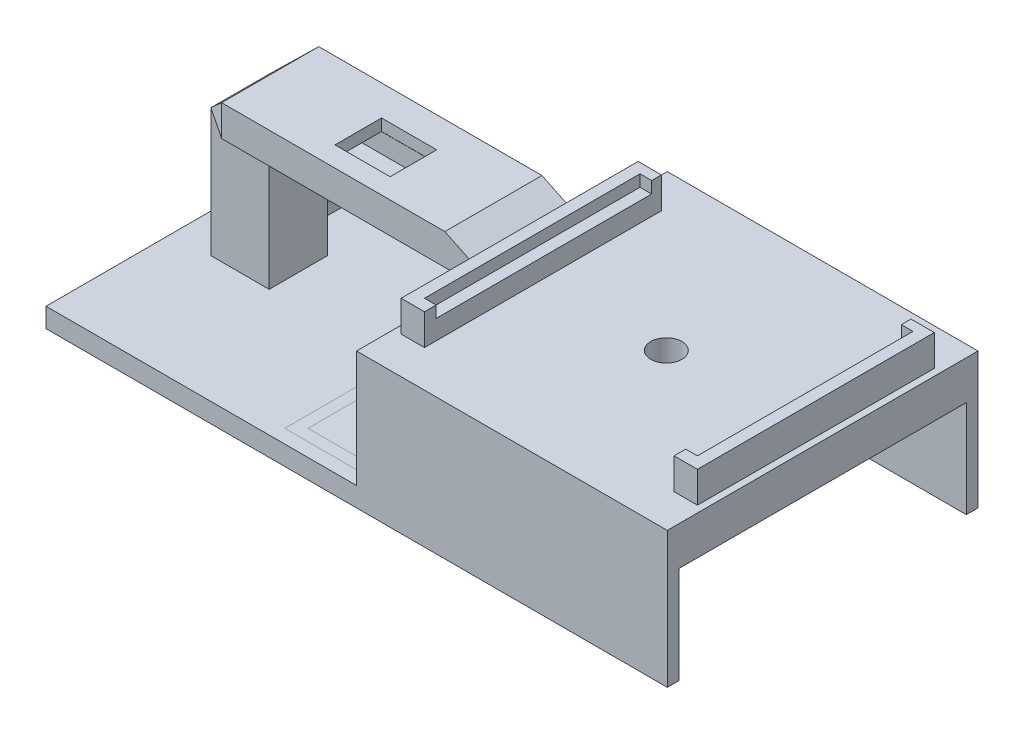
SolidWorks part; units mm, degrees
ref_plane "Plan de face" through (0, 0, 0) normal (0, 0, 1) x (1, 0, 0)
ref_plane "Plan de dessus" through (0, 0, 0) normal (0, 1, 0) x (1, 0, 0)
ref_plane "Plan de droite" through (0, 0, 0) normal (1, 0, 0) x (0, 0, -1)
sketch "Esquisse1" plane through (0, 0, 0) normal (0, 1, 0) x (1, 0, 0)
  line L1 (-75, 40) -> (75, 40)
  line L2 (-75, 40) -> (-75, -40)
  line L3 (-75, -40) -> (75, -40)
  line L4 (75, 40) -> (75, -40)
  line L5 (-75, 40) -> (75, -40) construction
  line L6 (-75, -40) -> (75, 40) construction
  point P0 (0, 0)
  dimension "D1" = 80
  dimension "D2" = 150
extrude "Boss.-Extru.1" add sketch "Esquisse1" along normal blind 5
sketch "Esquisse2" plane through (0, 5, 0) normal (0, 1, 0) x (1, 0, 0)
  line L0 (-75, -40) -> (75, -40) construction
  line L1 (75, 40) -> (-5, 40)
  line L2 (75, 40) -> (75, -40)
  line L3 (75, -40) -> (-5, -40)
  line L4 (-5, 40) -> (-5, -40)
  dimension "D1" = 80
extrude "Boss.-Extru.2" add sketch "Esquisse2" along normal blind 30
sketch "Esquisse3" plane through (0, 0, 0) normal (0, -1, 0) x (1, 0, 0)
  line L0 (75, -40) -> (-75, -40) construction
  line L1 (75, 40) -> (0, 40)
  line L2 (75, 40) -> (75, -40)
  line L3 (75, -40) -> (0, -40)
  line L4 (0, 40) -> (0, -40)
  dimension "D1" = 75
extrude "Enlèv. mat.-Extru.1" cut sketch "Esquisse3" against normal blind 25
sketch "Esquisse6" plane through (0, 35, 0) normal (0, 1, 0) x (1, 0, 0)
  circle A0 centre (34.7534, 0) radius 4
  dimension "D1" = 8
extrude "Enlèv. mat.-Extru.2" cut sketch "Esquisse6" against normal blind 40
sketch "Esquisse7" plane through (0, 35, 0) normal (0, 1, 0) x (1, 0, 0)
  line L0 (-5, 0) -> (75, 0) construction
  line L1 (-5, 40) -> (-5, -40) construction
  line L2 (75, -40) -> (75, 40) construction
  line L3 (70.2558, 0) -> (-0.0157, 0) construction
  line L4 (-3.0157, -30.5) -> (2.9843, -30.5)
  line L5 (-3.0157, -30.5) -> (-3.0157, 30.5)
  line L6 (-3.0157, 30.5) -> (2.9843, 30.5)
  line L7 (2.9843, -30.5) -> (2.9843, 30.5)
  line L8 (-3.0157, -30.5) -> (2.9843, 30.5) construction
  line L9 (-3.0157, 30.5) -> (2.9843, -30.5) construction
  line L10 (73.2558, -30.5) -> (67.2558, -30.5)
  line L11 (73.2558, -30.5) -> (73.2558, 30.5)
  line L12 (73.2558, 30.5) -> (67.2558, 30.5)
  line L13 (67.2558, -30.5) -> (67.2558, 30.5)
  line L14 (73.2558, -30.5) -> (67.2558, 30.5) construction
  line L15 (73.2558, 30.5) -> (67.2558, -30.5) construction
  point P6 (-0.0157, 0)
  point P11 (70.2558, 0)
  dimension "D1" = 6
  dimension "D2" = 61
  dimension "D3" = 6
  dimension "D4" = 61
  dimension "D5" = 69.9339
extrude "Boss.-Extru.3" add sketch "Esquisse7" along normal blind 8
sketch "Esquisse9" plane through (0, 5, 0) normal (0, 1, 0) x (1, 0, 0)
  line L0 (-5, 40) -> (-5, -40) construction
  line L1 (-5, -36.4789) -> (-27, -36.4789)
  line L2 (-5, -36.4789) -> (-5, -33.4789)
  line L3 (-5, -33.4789) -> (-27, -33.4789)
  line L4 (-27, -36.4789) -> (-27, -33.4789)
  line L6 (-27, -33.4789) -> (-24, -33.4789)
  line L7 (-27, -33.4789) -> (-27, 16.5211)
  line L8 (-27, 16.5211) -> (-24, 16.5211)
  line L9 (-24, -33.4789) -> (-24, 16.5211)
  line M4 (-5, -40) -> (-5, 40)
  dimension "D1" = 3
  dimension "D2" = 22
  dimension "D3" = 3
  dimension "D4" = 50
extrude "Boss.-Extru.4" add sketch "Esquisse9" along normal blind 0.0001 contours L4 L1 L3 M4 | L3 L9 L8 L7
sketch "Esquisse10" plane through (0, 43, 0) normal (0, 1, 0) x (1, 0, 0)
  line L0 (-0.0157, -30.5) -> (-0.0157, -27.5) construction
  line L1 (-3.0157, -30.5) -> (2.9843, -30.5) construction
  line L3 (-0.0157, -27.5) -> (2.9843, -27.5)
  line L4 (-0.0157, -27.5) -> (-0.0157, 28)
  line L5 (-0.0157, 28) -> (2.9843, 28)
  line L6 (2.9843, -27.5) -> (2.9843, 28)
  dimension "D1" = 3
  dimension "D2" = 3
  dimension "D3" = 55.5
extrude "Enlèv. mat.-Extru.3" cut sketch "Esquisse10" against normal blind 3
sketch "Esquisse11" plane through (0, 43, 0) normal (0, 1, 0) x (1, 0, 0)
  line L0 (70.2558, -30.5) -> (70.2558, -27.5) construction
  line L1 (67.2558, -30.5) -> (73.2558, -30.5) construction
  line L2 (67.2558, 30.5) -> (67.2558, -30.5) construction
  line L3 (70.2558, -27.5) -> (67.2558, -27.5)
  line L4 (70.2558, -27.5) -> (70.2558, 28)
  line L5 (70.2558, 28) -> (67.2558, 28)
  line L6 (67.2558, -27.5) -> (67.2558, 28)
  dimension "D1" = 3
  dimension "D2" = 55.5
extrude "Enlèv. mat.-Extru.4" cut sketch "Esquisse11" against normal blind 3
sketch "Esquisse12" plane through (0, 5, 0) normal (0, 1, 0) x (1, 0, 0)
  line L0 (-75, 0) -> (-5, 0) construction
  line L1 (-75, 40) -> (-75, -40) construction
  line L2 (-5, 40) -> (-5, -33.4789) construction
  line L4 (-60, -7.5) -> (-75, -7.5)
  line L5 (-60, -7.5) -> (-60, 7.5)
  line L6 (-60, 7.5) -> (-75, 7.5)
  line L7 (-75, -7.5) -> (-75, 7.5)
  line L8 (-60, -7.5) -> (-75, 7.5) construction
  line L9 (-60, 7.5) -> (-75, -7.5) construction
  point P7 (-67.5, 0)
  dimension "D1" = 15
  dimension "D2" = 15
extrude "Boss.-Extru.5" add sketch "Esquisse12" along normal blind 40
sketch "Esquisse13" plane through (0, 45, 0) normal (0, 1, 0) x (1, 0, 0)
  line L0 (-22.7295, -13.0071) -> (-66.7295, -13.0071)
  line L5 (-22.7295, -13.0071) -> (-22.7295, 11.9929)
  line L6 (-66.7295, -13.0071) -> (-66.7295, 11.9929)
  line L7 (-22.7295, 11.9929) -> (-66.7295, 11.9929)
  line L8 (-22.7295, -13.0071) -> (-66.7295, 11.9929) construction
  line L9 (-66.7295, -13.0071) -> (-22.7295, 11.9929) construction
  point P1 (-44.7295, -0.5071)
  dimension "D1" = 25
  dimension "D2" = 44
extrude "Boss.-Extru.6" add sketch "Esquisse13" along normal blind 1 and the other way blind 7
sketch "Esquisse14" plane through (0, 45, 0) normal (0, 1, 0) x (1, 0, 0)
  line L0 (-66.7295, -13.0071) -> (-75, -7.5)
  line L1 (-75, -7.5) -> (-75, 7.5)
  line L2 (-75, 7.5) -> (-66.7295, 11.9929)
  line L3 (-66.7295, 11.9929) -> (-66.7295, -13.0071)
extrude "Boss.-Extru.7" add sketch "Esquisse14" along normal blind 1 and the other way blind 7
ref_plane "Plan1" through (0, 38, 0) normal (0, 1, 0) x (1, 0, 0)
sketch "Esquisse16" plane through (0, 38, 0) normal (0, -1, 0) x (1, 0, 0)
  line L1 (-51.5, 7.8693) -> (-28.5, 7.8693)
  line L2 (-51.5, 7.8693) -> (-51.5, -4.1307)
  line L3 (-51.5, -4.1307) -> (-28.5, -4.1307)
  line L4 (-28.5, 7.8693) -> (-28.5, -4.1307)
  line L5 (-51.5, 7.8693) -> (-28.5, -4.1307) construction
  line L6 (-51.5, -4.1307) -> (-28.5, 7.8693) construction
  point P0 (-40, 1.8693)
  dimension "D1" = 12
  dimension "D2" = 23
extrude "Enlèv. mat.-Extru.5" cut sketch "Esquisse16" against normal blind 5
sketch "Esquisse17" plane through (0, 43, 0) normal (0, -1, 0) x (1, 0, 0)
  line L1 (-28.5375, 8.2239) -> (-42.7375, 8.2239)
  line L2 (-28.5375, 8.2239) -> (-28.5375, -3.7761)
  line L3 (-28.5375, -3.7761) -> (-42.7375, -3.7761)
  line L4 (-42.7375, 8.2239) -> (-42.7375, -3.7761)
  dimension "D1" = 12
  dimension "D2" = 14.2
sketch "Esquisse18" plane through (0, 43, 0) normal (0, -1, 0) x (1, 0, 0)
  line L0 (-42.7375, 8.2239) -> (-42.7375, -3.7761) construction
  line L1 (-28.5375, -4.1729) -> (-42.7375, -4.1729)
  line L2 (-28.5375, -4.1729) -> (-28.5375, 7.8271)
  line L3 (-28.5375, 7.8271) -> (-42.7375, 7.8271)
  line L4 (-42.7375, -4.1729) -> (-42.7375, 7.8271)
  dimension "D1" = 12
  dimension "D2" = 14.2
extrude "Enlèv. mat.-Extru.7" cut sketch "Esquisse18" against normal blind 5
sketch "Esquisse19" plane through (-22.7295, 0, 0) normal (1, 0, 0) x (0, 0, -1)
  line L1 (-13.0071, 38) -> (11.9929, 38)
  line L2 (-13.0071, 38) -> (-13.0071, 46)
  line L3 (-13.0071, 46) -> (11.9929, 46)
  line L4 (11.9929, 38) -> (11.9929, 46)
extrude "Boss.-Extru.8" add sketch "Esquisse19" along normal blind 20
sketch "Esquisse20" plane through (0, 0, -11.9929) normal (0, 0, -1) x (-1, 0, 0)
  line L0 (3.0157, 43) -> (9.2631, 46)
  line L1 (2.7295, 46) -> (66.7295, 46) construction
  line L2 (9.2631, 46) -> (2.7295, 46)
  line L3 (2.7295, 46) -> (2.7295, 43)
  line L4 (2.7295, 43) -> (3.0157, 43)
extrude "Enlèv. mat.-Extru.8" cut sketch "Esquisse20" against normal through all
sketch "Esquisse21" plane through (0, 0, -11.9929) normal (0, 0, -1) x (-1, 0, 0)
  line L0 (3.0157, 38) -> (66.7295, 38) construction
  line L1 (3.0157, 35) -> (5, 35)
  line L2 (3.0157, 35) -> (3.0157, 38)
  line L3 (3.0157, 38) -> (5, 38)
  line L4 (5, 35) -> (5, 38)
extrude "Boss.-Extru.9" add sketch "Esquisse21" against normal blind 25
sketch "Esquisse22" plane through (0, 0, 0) normal (1, 0, 0) x (0, 0, -1)
  line L0 (-40, 0) -> (40, 0) construction
  line L1 (-40, 25) -> (-37, 25)
  line L2 (-40, 25) -> (-40, 0)
  line L3 (-40, 0) -> (-37, 0)
  line L4 (-37, 25) -> (-37, 0)
  dimension "D1" = 3
extrude "Boss.-Extru.10" add sketch "Esquisse22" along normal blind 75
mirror "Symétrie1" about plane through (0, 0, 0) normal (0, 0, 1) of "Boss.-Extru.10"
sketch "Esquisse23" plane through (-75, 0, 0) normal (-1, 0, 0) x (0, 0, 1)
  line L1 (-40, 5) -> (40, 5)
  line L2 (-40, 5) -> (-40, 0)
  line L3 (-40, 0) -> (40, 0)
  line L4 (40, 5) -> (40, 0)
extrude "Boss.-Extru.11" add sketch "Esquisse23" along normal blind 9.96
sketch "Esquisse24" plane through (0, 5, 4.1938) normal (0, 1, 0) x (1, 0, 0)
  line L1 (-80.3301, 33.5428) -> (-68.9134, 33.5428)
  line L2 (-80.3301, 33.5428) -> (-80.3301, 17.0949)
  line L3 (-80.3301, 17.0949) -> (-68.9134, 17.0949)
  line L4 (-68.9134, 33.5428) -> (-68.9134, 17.0949)
  line L5 (-80.3301, 33.5428) -> (-68.9134, 17.0949) construction
  line L6 (-80.3301, 17.0949) -> (-68.9134, 33.5428) construction
  point P0 (-74.6218, 25.3189)
extrude "Boss.-Extru.12" add sketch "Esquisse24" along normal blind 3
sketch "Esquisse25" plane through (0, 0, 7.5) normal (0, 0, 1) x (1, 0, 0)
  line L0 (-75, 38) -> (-66.7295, 46)
extrude "Enlèv. mat.-Extru.9" cut sketch "Esquisse25" against normal through all and the other way through all
